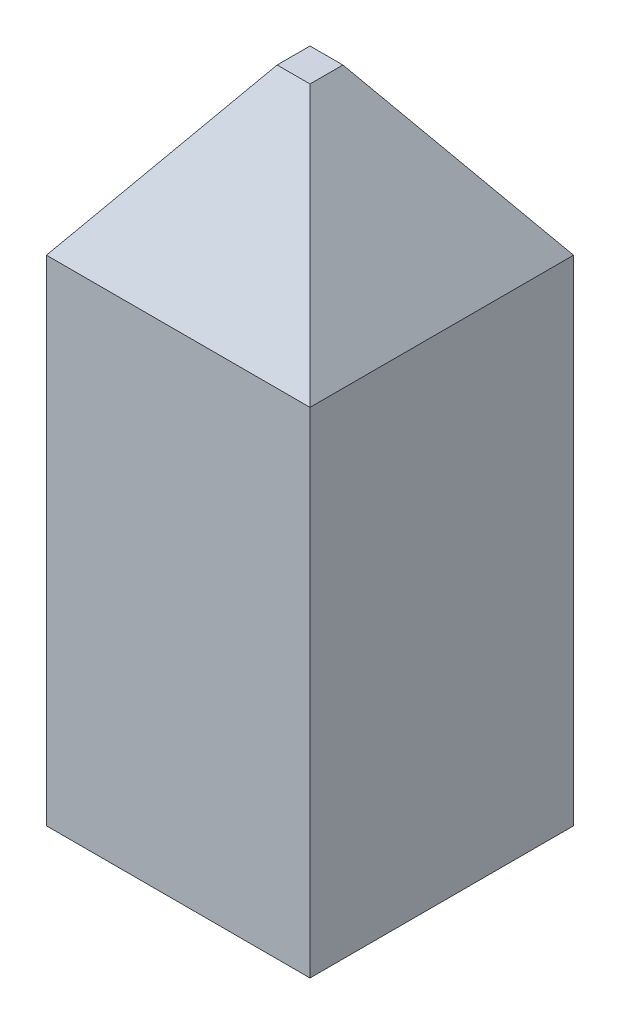
SolidWorks part; units mm, degrees
ref_plane "Front Plane" through (0, 0, 0) normal (0, 0, 1) x (1, 0, 0)
ref_plane "Top Plane" through (0, 0, 0) normal (0, 1, 0) x (1, 0, 0)
ref_plane "Right Plane" through (0, 0, 0) normal (1, 0, 0) x (0, 0, -1)
sketch "Sketch1" plane through (0, 0, 0) normal (0, 1, 0) x (1, 0, 0)
  line L1 (-0.2, -0.2) -> (0.2, -0.2)
  line L2 (-0.2, -0.2) -> (-0.2, 0.2)
  line L3 (-0.2, 0.2) -> (0.2, 0.2)
  line L4 (0.2, -0.2) -> (0.2, 0.2)
  line L5 (-0.2, -0.2) -> (0.2, 0.2) construction
  line L6 (-0.2, 0.2) -> (0.2, -0.2) construction
  point P0 (0, 0)
  dimension "D1" = 0.4
  dimension "D2" = 0.4
extrude "Boss-Extrude1" add sketch "Sketch1" along normal blind 0.75
sketch "Sketch2" plane through (0, 0.75, 0) normal (0, 1, 0) x (1, 0, 0)
  line L4 (0.2, -0.2) -> (0.2, 0.2)
  line L5 (0.2, 0.2) -> (-0.2, 0.2)
  line L6 (-0.2, 0.2) -> (-0.2, -0.2)
  line L7 (-0.2, -0.2) -> (0.2, -0.2)
  line L8 (0.2, -0.2) -> (0.2, 0.2)
  line L9 (0.2, 0.2) -> (-0.2, 0.2)
  line L10 (-0.2, 0.2) -> (-0.2, -0.2)
  line L11 (-0.2, -0.2) -> (0.2, -0.2)
  dimension "D1" = 0
extrude "Boss-Extrude2" add sketch "Sketch2" along normal blind 0.25 draft 35
